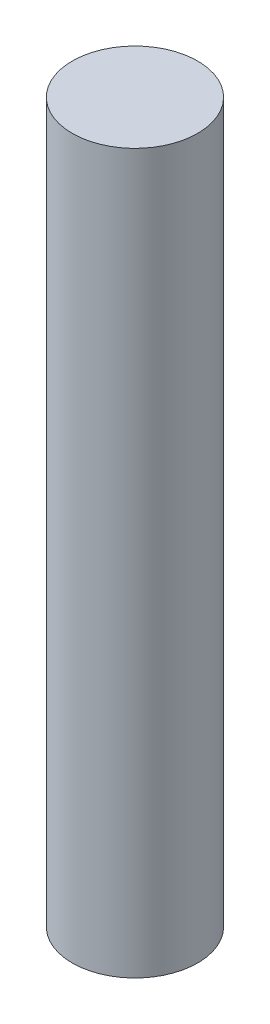
SolidWorks part; units mm, degrees
ref_plane "Front Plane" through (0, 0, 0) normal (0, 0, 1) x (1, 0, 0)
ref_plane "Top Plane" through (0, 0, 0) normal (0, 1, 0) x (1, 0, 0)
ref_plane "Right Plane" through (0, 0, 0) normal (1, 0, 0) x (0, 0, -1)
sketch "Sketch1" plane through (0, 0, 0) normal (0, 1, 0) x (1, 0, 0)
  circle A0 centre (0, 0) radius 0.815
  dimension "D1" = 1.63
extrude "Boss-Extrude1" add sketch "Sketch1" along normal blind 9.34
